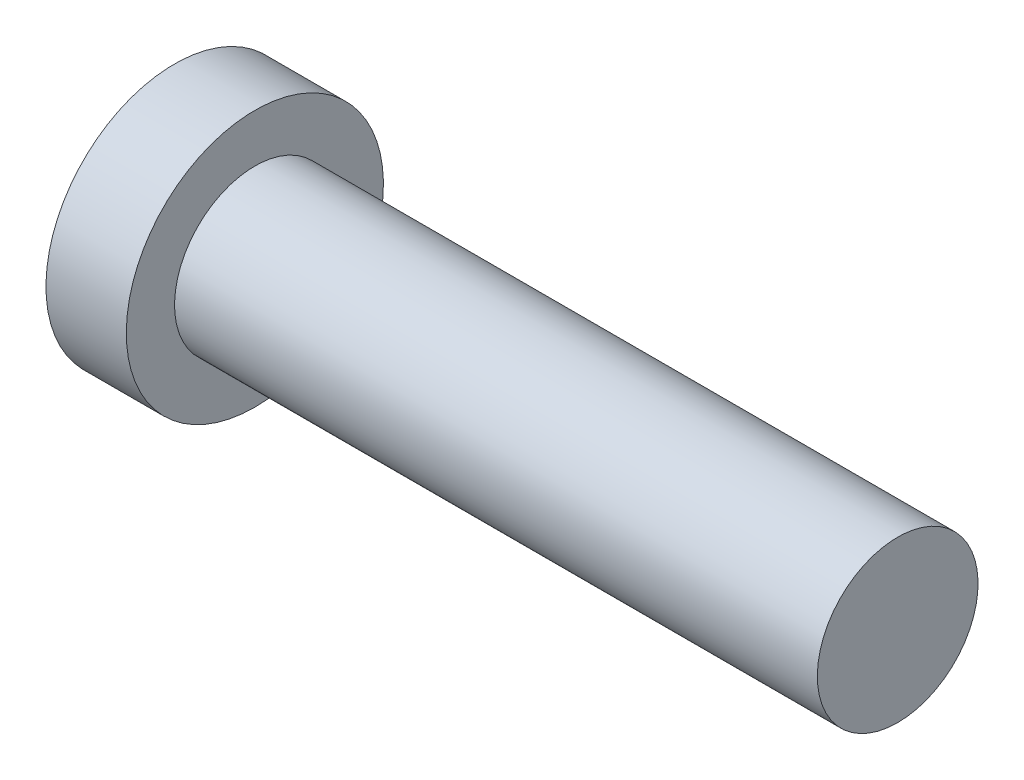
SolidWorks part; units mm, degrees
ref_plane "Front Plane" through (0, 0, 0) normal (0, 0, 1) x (1, 0, 0)
ref_plane "Top Plane" through (0, 0, 0) normal (0, 1, 0) x (1, 0, 0)
ref_plane "Right Plane" through (0, 0, 0) normal (1, 0, 0) x (0, 0, -1)
sketch "Sketch1" plane through (0, 0, 0) normal (0, 0, 1) x (1, 0, 0)
  line L0 (0, 0) -> (0, 0.25)
  line L1 (0, 0.25) -> (-2, 0.25)
  line L2 (-2, 0.25) -> (-2, 0.4)
  line L3 (-2, 0.4) -> (-2.25, 0.4)
  line L4 (-2.25, 0.4) -> (-2.25, 0)
  line L5 (-2.25, 0) -> (0, 0) construction
  line L6 (0, 0) -> (-2.25, 0)
  dimension "D1" = 0.25
  dimension "D2" = 0.4
  dimension "D3" = 0.4
  dimension "D4" = 2
  dimension "D5" = 0.25
revolve "Revolve1" add sketch "Sketch1" angle 360 about L5
